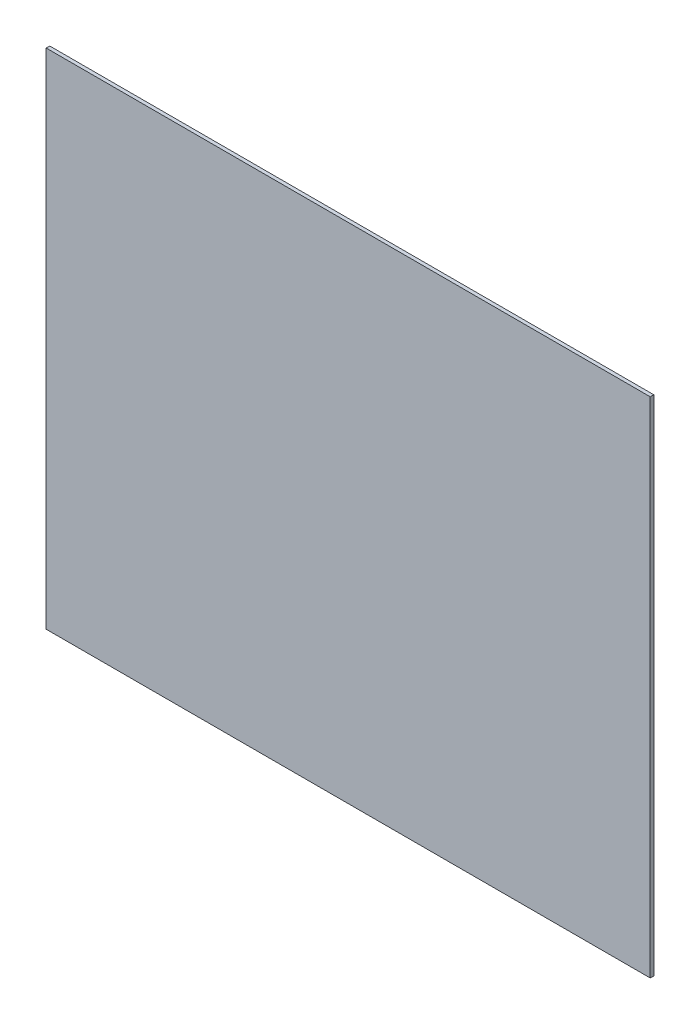
SolidWorks part; units mm, degrees
ref_plane "Přední rovina" through (0, 0, 0) normal (0, 0, 1) x (1, 0, 0)
ref_plane "Horní rovina" through (0, 0, 0) normal (0, 1, 0) x (1, 0, 0)
ref_plane "Pravá rovina" through (0, 0, 0) normal (1, 0, 0) x (0, 0, -1)
sketch "Skica1" plane through (0, 0, 0) normal (0, 0, 1) x (1, 0, 0)
  line L1 (-255, 212.5) -> (255, 212.5)
  line L2 (-255, 212.5) -> (-255, -212.5)
  line L3 (-255, -212.5) -> (255, -212.5)
  line L4 (255, 212.5) -> (255, -212.5)
  line L5 (-255, 212.5) -> (255, -212.5) construction
  line L6 (-255, -212.5) -> (255, 212.5) construction
  point P0 (0, 0)
  dimension "D1" = 510
  dimension "D2" = 425
extrude "Přidat vysunutím1" add sketch "Skica1" along normal blind 3
